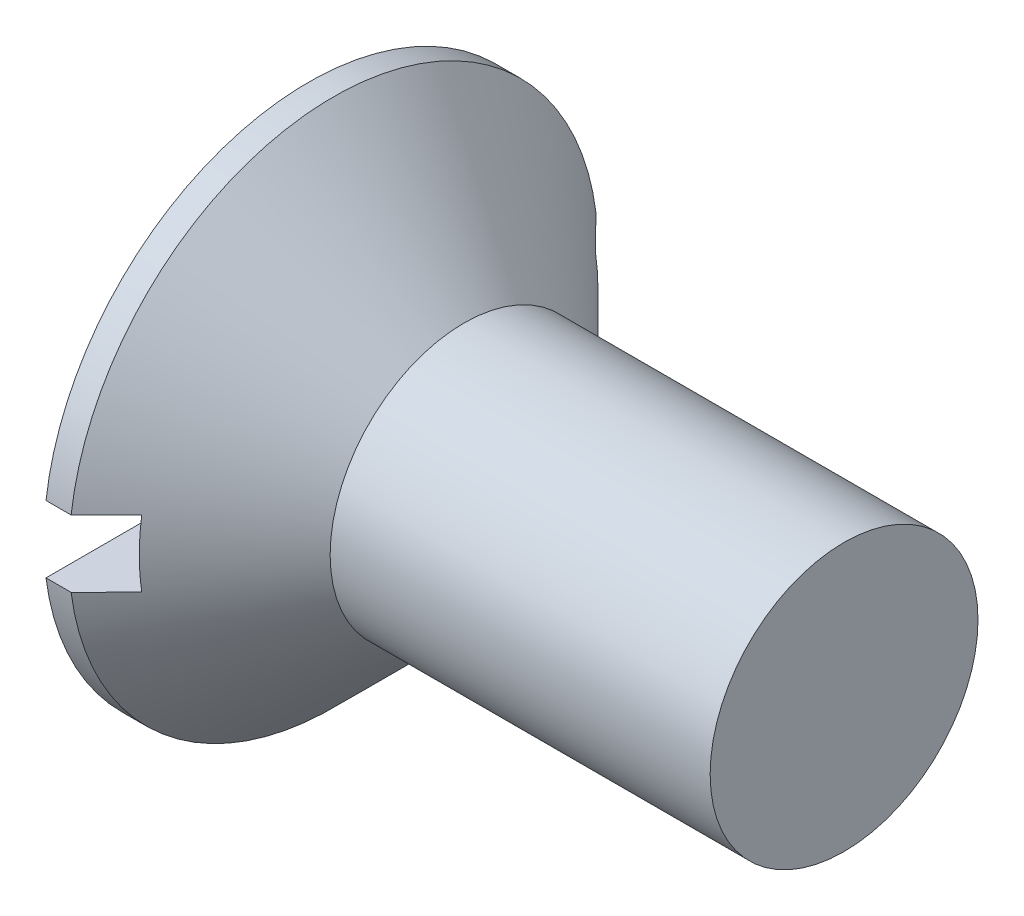
SolidWorks part; units mm, degrees
material "Q235A"
ref_plane "前视基准面" through (0, 0, 0) normal (0, 0, 1) x (1, 0, 0)
ref_plane "上视基准面" through (0, 0, 0) normal (0, 1, 0) x (1, 0, 0)
ref_plane "右视基准面" through (0, 0, 0) normal (1, 0, 0) x (0, 0, -1)
sketch "草图1" plane through (0, 0, 0) normal (0, 0, 1) x (1, 0, 0)
  line L0 (-3.2286, 0) -> (28.4564, 0) construction
  line L1 (0, 0) -> (0, 7.9)
  line L2 (0, 7.9) -> (0.75, 7.9)
  line L3 (0.75, 7.9) -> (4.65, 4)
  line L4 (4.65, 4) -> (16, 4)
  line L5 (16, 4) -> (16, 0)
  line L6 (0, 0) -> (16, 0)
  dimension "D1" = 16
  dimension "D2" = 8
  dimension "D3" = 45
  dimension "D4" = 15.8
  dimension "D5" = 4.65
revolve "旋转1" add sketch "草图1" angle 360 about L0
cosmetic thread "装饰螺纹线1" parameters "D2"=6.647
sketch "草图2" plane through (0, 0, 0) normal (0, 0, 1) x (1, 0, 0)
  line L0 (-3.2286, 0) -> (28.4564, 0) construction
  line L1 (-0.4896, -1) -> (1.8, -1)
  line L2 (-0.4896, -1) -> (-0.4896, 1)
  line L3 (-0.4896, 1) -> (1.8, 1)
  line L4 (1.8, -1) -> (1.8, 1)
  line L5 (-3.2286, 0) -> (28.4564, 0) construction
  line L6 (0, 0) -> (0, 7.9) construction
  dimension "D1" = 2
  dimension "D2" = 1.8
extrude "切除-拉伸1" cut sketch "草图2" against normal through all and the other way through all
